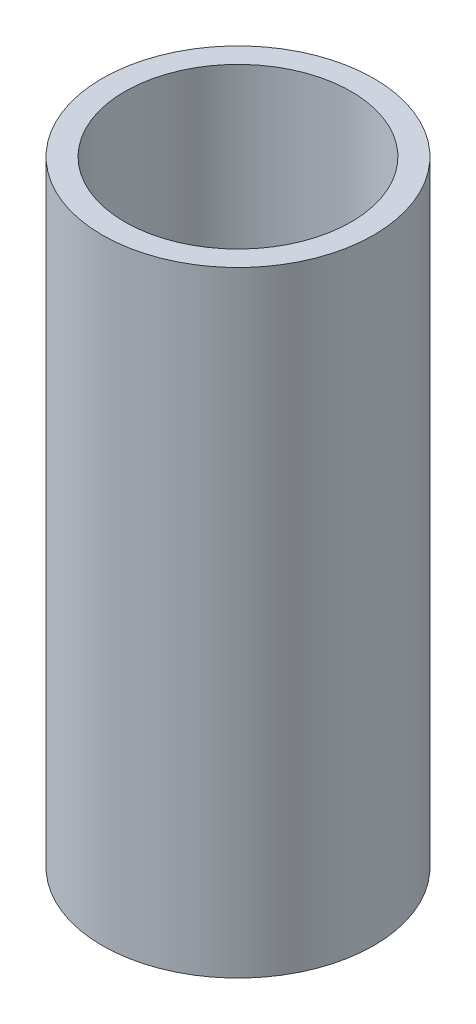
SolidWorks part; units mm, degrees
ref_plane "Front Plane" through (0, 0, 0) normal (0, 0, 1) x (1, 0, 0)
ref_plane "Top Plane" through (0, 0, 0) normal (0, 1, 0) x (1, 0, 0)
ref_plane "Right Plane" through (0, 0, 0) normal (1, 0, 0) x (0, 0, -1)
sketch "Sketch1" plane through (0, 0, 0) normal (0, 1, 0) x (1, 0, 0)
  circle A0 centre (0, 2.2789) radius 9.525
  circle A2 centre (0, 2.2789) radius 7.9375
  dimension "D1" = 1.5875
  dimension "D2" = 19.05
extrude "Boss-Extrude1" add sketch "Sketch1" along normal blind 43.18
